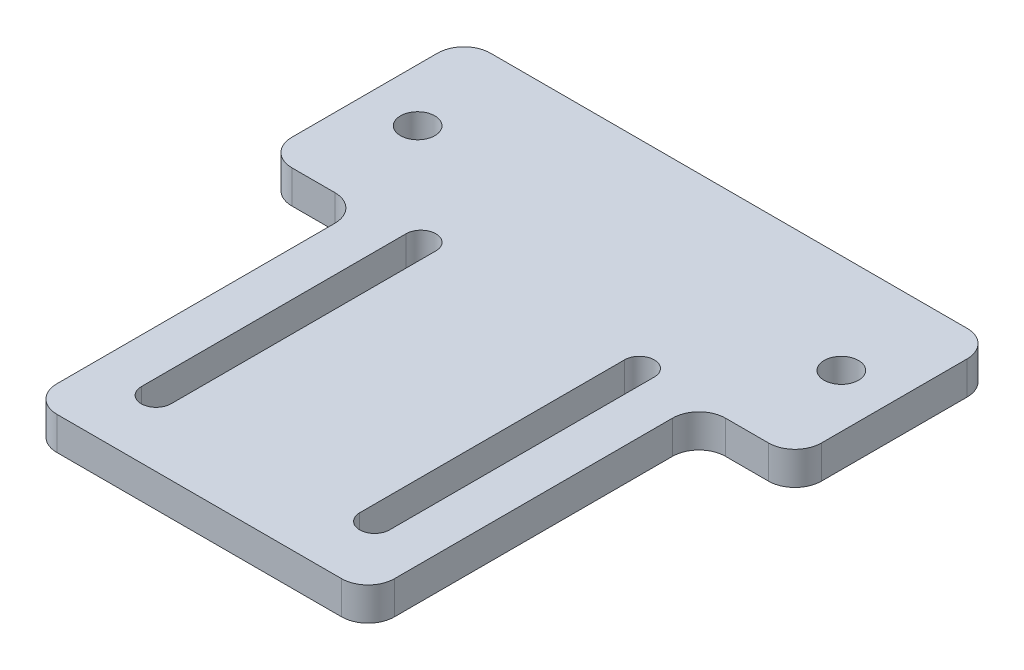
SolidWorks part; units mm, degrees
ref_plane "前视基准面" through (0, 0, 0) normal (0, 0, 1) x (1, 0, 0)
ref_plane "上视基准面" through (0, 0, 0) normal (0, 1, 0) x (1, 0, 0)
ref_plane "右视基准面" through (0, 0, 0) normal (1, 0, 0) x (0, 0, -1)
other "Configuration Table"
sketch "草图1" plane through (0, 0, 0) normal (0, 1, 0) x (1, 0, 0)
  line L0 (-40, 0) -> (-25.5, 0)
  line L1 (-40, 0) -> (-40, 30)
  line L2 (-40, 30) -> (40, 30)
  line L3 (40, 30) -> (40, 0)
  line L4 (-25.5, 0) -> (-25.5, -50)
  line L5 (-25.5, -50) -> (25.5, -50)
  line L6 (25.5, -50) -> (25.5, 0)
  line L7 (16.5, 0) -> (16.5, -40) construction
  line L8 (18.75, 0) -> (18.75, -40)
  line L9 (14.25, 0) -> (14.25, -40)
  line L10 (0, 0) -> (0, -50) construction
  line L11 (-16.5, 0) -> (-16.5, -40) construction
  line L12 (-18.75, 0) -> (-18.75, -40)
  line L13 (-14.25, 0) -> (-14.25, -40)
  line L14 (25.5, 0) -> (40, 0)
  arc A0 (18.75, 0) -> (14.25, 0) centre (16.5, 0) ccw
  arc A1 (14.25, -40) -> (18.75, -40) centre (16.5, -40) ccw
  arc A2 (-18.75, 0) -> (-14.25, 0) centre (-16.5, 0) cw
  arc A3 (-14.25, -40) -> (-18.75, -40) centre (-16.5, -40) cw
  circle A4 centre (-32, 15) radius 2.6
  circle A6 centre (32, 15) radius 2.6
  point P8 (0, -50)
  point P11 (16.5, -20)
  point P22 (-16.5, -20)
  point P30 (-40, 15)
  dimension "D5" = 2.25
  dimension "D7" = 5.2
  dimension "D8" = 8
  dimension "D9" = 0
  dimension "D1" = 80
  dimension "D2" = 51
  dimension "D3" = 30
  dimension "D4" = 50
  dimension "D6" = 33
  dimension "D10" = 40
extrude "凸台-拉伸1" add sketch "草图1" along normal blind 5
fillet "圆角1" radius 4 8 edges at (-40, 2.5, -30) (40, 2.5, -30) (40, 2.5, 0) (25.5, 2.5, 0) (25.5, 2.5, 50) (-25.5, 2.5, 50) (-25.5, 2.5, 0) (-40, 2.5, 0)
